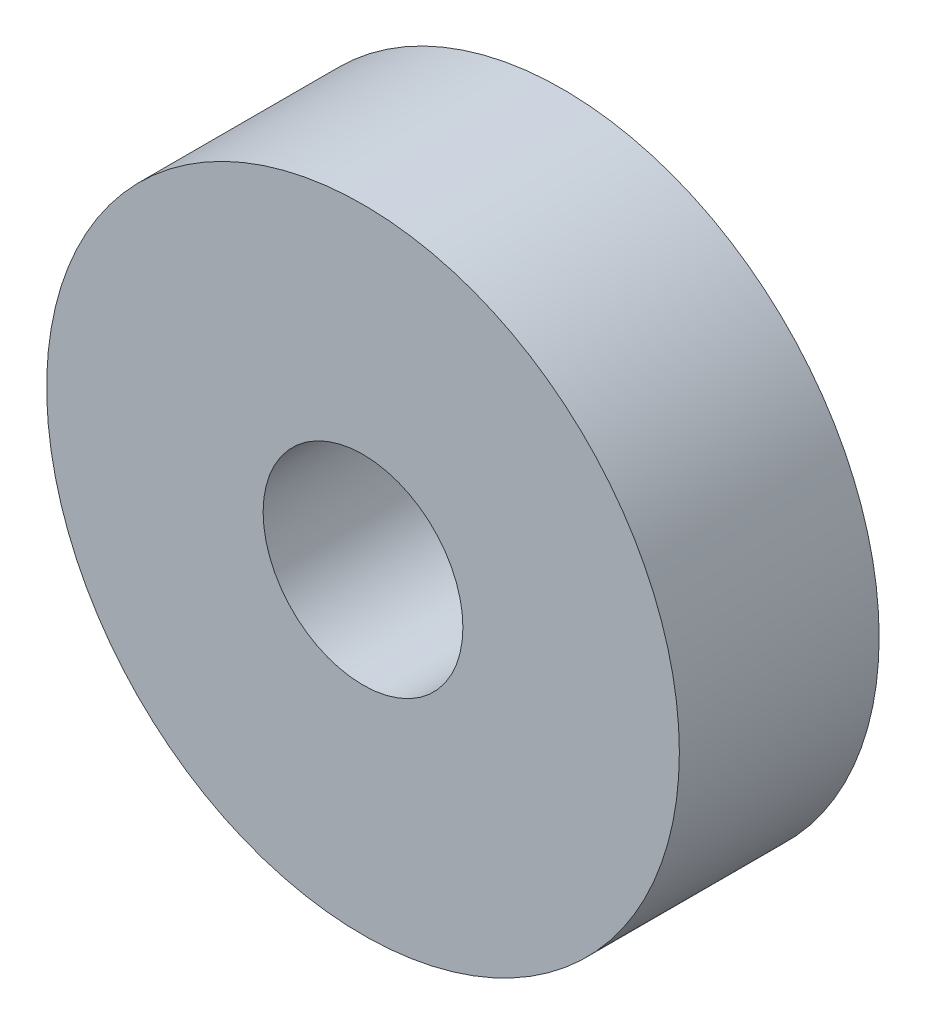
SolidWorks part; units mm, degrees
ref_plane "正面" through (0, 0, 0) normal (0, 0, 1) x (1, 0, 0)
ref_plane "平面" through (0, 0, 0) normal (0, 1, 0) x (1, 0, 0)
ref_plane "右側面" through (0, 0, 0) normal (1, 0, 0) x (0, 0, -1)
sketch "ｽｹｯﾁ1" plane through (0, 0, 0) normal (0, 0, 1) x (1, 0, 0)
  circle A0 centre (0, 0) radius 9.5
  circle A1 centre (0, 0) radius 3
  dimension "D1" = 19
  dimension "D2" = 6
extrude "ﾎﾞｽ - 押し出し1" add sketch "ｽｹｯﾁ1" along normal blind 6
